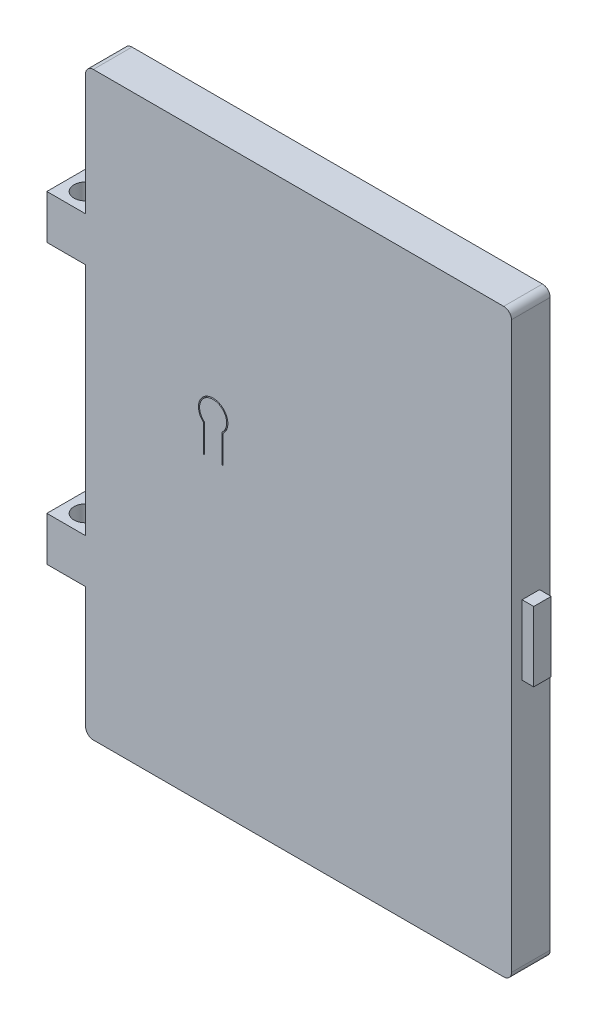
SolidWorks part; units mm, degrees
ref_plane "Front Plane" through (0, 0, 0) normal (0, 0, 1) x (1, 0, 0)
ref_plane "Top Plane" through (0, 0, 0) normal (0, 1, 0) x (1, 0, 0)
ref_plane "Right Plane" through (0, 0, 0) normal (1, 0, 0) x (0, 0, -1)
sketch "Sketch1" plane through (0, 0, 0) normal (0, 0, 1) x (1, 0, 0)
  line L1 (0, 0) -> (110, 0)
  line L2 (0, 0) -> (0, 150)
  line L3 (0, 150) -> (110, 150)
  line L4 (110, 0) -> (110, 150)
  dimension "D1" = 150
  dimension "D2" = 110
extrude "Boss-Extrude1" add sketch "Sketch1" along normal blind 10
sketch "Sketch2" plane through (0, 0, 0) normal (0, 0, -1) x (-1, 0, 0)
  line L0 (-110, 0) -> (-110, 150) construction
  line L1 (-93, 53) -> (-7, 53)
  line L2 (-95, 55) -> (-95, 113)
  line L3 (-93, 115) -> (-7, 115)
  line L4 (-5, 55) -> (-5, 113)
  line L5 (0, 150) -> (0, 0) construction
  line L6 (-110, 150) -> (0, 150) construction
  arc A0 (-7, 115) -> (-5, 113) centre (-7, 113) cw
  arc A1 (-5, 55) -> (-7, 53) centre (-7, 55) cw
  arc A2 (-95, 55) -> (-93, 53) centre (-93, 55) ccw
  arc A3 (-95, 113) -> (-93, 115) centre (-93, 113) cw
  dimension "D5" = 2
  dimension "D1" = 15
  dimension "D2" = 5
  dimension "D3" = 62
  dimension "D4" = 35
extrude "Cut-Extrude1" cut sketch "Sketch2" against normal blind 6
sketch "Sketch3" plane through (0, 0, 6) normal (0, 0, -1) x (-1, 0, 0)
  line L0 (-95, 113) -> (-95, 55) construction
  line L1 (-91.46, 95.2) -> (-91.46, 58.2) construction
  line L2 (-91.46, 58.2) -> (-51.96, 58.2) construction
  line L3 (-51.96, 58.2) -> (-24.96, 58.2) construction
  line L4 (-24.96, 58.2) -> (-9.46, 76.2) construction
  line L5 (-9.46, 76.2) -> (-9.46, 110.2) construction
  line L6 (-9.46, 110.2) -> (-70.96, 111.2) construction
  line L7 (-70.96, 111.2) -> (-91.46, 95.2) construction
  line L8 (-93, 53) -> (-7, 53) construction
  circle A0 centre (-91.46, 95.2) radius 2.5
  circle A1 centre (-70.96, 111.2) radius 2.5
  circle A2 centre (-9.46, 110.2) radius 2.5
  circle A3 centre (-9.46, 76.2) radius 2.5
  circle A4 centre (-24.96, 58.2) radius 2.5
  circle A5 centre (-51.96, 58.2) radius 2.5
  circle A6 centre (-91.46, 58.2) radius 2.5
  dimension "D1" = 5
  dimension "D2" = 5.2
  dimension "D4" = 52
  dimension "D3" = 3.54
  dimension "D5" = 82
  dimension "D6" = 18
  dimension "D7" = 66.5
  dimension "D8" = 39.5
  dimension "D9" = 20.5
  dimension "D10" = 37
  dimension "D11" = 53
extrude "Boss-Extrude2" add sketch "Sketch3" along normal blind 18
sketch "Sketch5" plane through (0, 0, 0) normal (0, 0, 1) x (1, 0, 0)
  circle A0 centre (91.46, 58.2) radius 1.1
  circle A1 centre (51.96, 58.2) radius 1.1
  circle A2 centre (24.96, 58.2) radius 1.1
  circle A3 centre (9.46, 76.2) radius 1.1
  circle A4 centre (9.46, 110.2) radius 1.1
  circle A5 centre (70.96, 111.2) radius 1.1
  circle A6 centre (91.46, 95.2) radius 1.1
  dimension "D1" = 2.2
extrude "Cut-Extrude2" cut sketch "Sketch5" along normal blind 5 from surface at -12 starting at face at (68.46, 111.2, -12)
sketch "Sketch6" plane through (0, 0, 6) normal (0, 0, -1) x (-1, 0, 0)
  line L0 (-87.5, 78) -> (-83.5, 78)
  line L1 (-89.5, 80) -> (-89.5, 91)
  line L2 (-87.5, 93) -> (-83.5, 93)
  line L3 (-81.5, 80) -> (-81.5, 91)
  line L4 (-7, 115) -> (-93, 115) construction
  line L5 (-95, 113) -> (-95, 55) construction
  arc A0 (-81.5, 91) -> (-83.5, 93) centre (-83.5, 91) ccw
  arc A1 (-87.5, 93) -> (-89.5, 91) centre (-87.5, 91) ccw
  arc A2 (-89.5, 80) -> (-87.5, 78) centre (-87.5, 80) ccw
  arc A3 (-81.5, 80) -> (-83.5, 78) centre (-83.5, 80) cw
  dimension "D5" = 2
  dimension "D1" = 22
  dimension "D2" = 5.5
  dimension "D3" = 15
  dimension "D4" = 8
extrude "Cut-Extrude3" cut sketch "Sketch6" against normal blind 4 from offset 0.5
sketch "Sketch7" plane through (0, 0, 6) normal (0, 0, -1) x (-1, 0, 0)
  line L0 (-7, 115) -> (-93, 115) construction
  line L1 (-5, 55) -> (-5, 113) construction
  circle A0 centre (-32.95, 88.15) radius 1.875
  dimension "D3" = 3.75
  dimension "D1" = 26.85
  dimension "D2" = 27.95
extrude "Boss-Extrude3" add sketch "Sketch7" along normal blind 11.5
sketch "Sketch8" plane through (0, 0, 10) normal (0, 0, 1) x (1, 0, 0)
  line L0 (30.7, 85.469) -> (35.2, 85.469) construction
  line L1 (30.7, 85.469) -> (30.7, 78.15)
  line L2 (30.7, 78.15) -> (35.2, 78.15)
  line L3 (35.2, 85.469) -> (35.2, 78.15)
  line L4 (30.4, 85.3326) -> (30.4, 78.15)
  line L5 (35.5, 85.3326) -> (35.5, 78.15)
  line L6 (30.4, 78.15) -> (35.5, 78.15)
  arc A0 (35.2, 85.469) -> (30.7, 85.469) centre (32.95, 88.15) ccw
  arc A2 (35.5, 85.3326) -> (30.4, 85.3326) centre (32.95, 88.15) ccw
  arc A3 (35.3929, 85.2393) -> (30.5071, 85.2393) centre (32.95, 88.15) ccw construction
  point P11 (0, 0)
  point P13 (30.3692, 85.3326)
  point P16 (0, 0)
  point P17 (35.5, 85.3326)
  point P18 (0, 0)
  point P19 (35.4956, 85.3326)
  dimension "D1" = 3.5
  dimension "D5" = 0.3
  dimension "D2" = 4.5
  dimension "D3" = 10
  dimension "D4" = 0.3
  dimension "D6" = 0.3
extrude "Cut-Extrude4" cut sketch "Sketch8" against normal blind 4 contours L5 A2 L4 L6 L1 A0 L3
sketch "Sketch9" plane through (0, 0, 0) normal (-1, 0, 0) x (0, 0, 1)
  line L0 (10, 75) -> (-10.2095, 75) construction
  line L1 (10, 150) -> (10, 0) construction
  line L2 (0, 150) -> (0, 0) construction
  line L3 (0, 97) -> (10, 97) construction
  line L4 (0, 97) -> (0, 105) construction
  line L5 (0, 105) -> (10, 105) construction
  line L6 (10, 97) -> (10, 105) construction
  line L7 (0, 117) -> (10, 117) construction
  line L8 (0, 117) -> (0, 125) construction
  line L9 (0, 125) -> (10, 125) construction
  line L10 (10, 117) -> (10, 125) construction
  line L11 (0, 33.3) -> (10, 33.3)
  line L12 (0, 105.3) -> (10, 105.3)
  line L13 (0, 105.3) -> (0, 116.7)
  line L14 (0, 116.7) -> (10, 116.7)
  line L15 (10, 105.3) -> (10, 116.7)
  line L16 (10, 44.7) -> (10, 33.3)
  line L17 (0, 44.7) -> (10, 44.7)
  line L18 (0, 44.7) -> (0, 33.3)
  dimension "D1" = 22
  dimension "D2" = 8
  dimension "D3" = 8
  dimension "D4" = 12
  dimension "D5" = 0.3
  dimension "D6" = 0.3
extrude "Boss-Extrude4" add sketch "Sketch9" along normal blind 10
sketch "Sketch10" plane through (0, 116.7, 0) normal (0, 1, 0) x (1, 0, 0)
  line L0 (-10, -10) -> (0, -10) construction
  line L2 (-10, -10) -> (-10, 0) construction
  circle A0 centre (-5, -5) radius 3
  dimension "D1" = 6
  dimension "D2" = 5
  dimension "D3" = 5
extrude "Cut-Extrude5" cut sketch "Sketch10" against normal through all
sketch "Sketch11" plane through (110, 0, 0) normal (1, 0, 0) x (0, 0, -1)
  line L0 (-10, 75) -> (0, 75) construction
  line L1 (-10, 0) -> (-10, 150) construction
  line L2 (0, 0) -> (0, 150) construction
  line L4 (-7.25, 84) -> (-2.75, 84)
  line L5 (-7.25, 84) -> (-7.25, 66)
  line L6 (-7.25, 66) -> (-2.75, 66)
  line L7 (-2.75, 84) -> (-2.75, 66)
  line L8 (-7.25, 84) -> (-2.75, 66) construction
  line L9 (-7.25, 66) -> (-2.75, 84) construction
  point P6 (-5, 75)
  dimension "D1" = 9
  dimension "D2" = 4.5
extrude "Boss-Extrude5" add sketch "Sketch11" along normal blind 3
sketch "Sketch12" plane through (0, 0, 10) normal (0, 0, 1) x (1, 0, 0)
  line L0 (197.986, 597.4226) -> (880.6527, 597.4226) construction
fillet "Fillet1" radius 2 4 edges at (0, 0, 5) (110, 0, 5) (110, 150, 5) (0, 150, 5)
